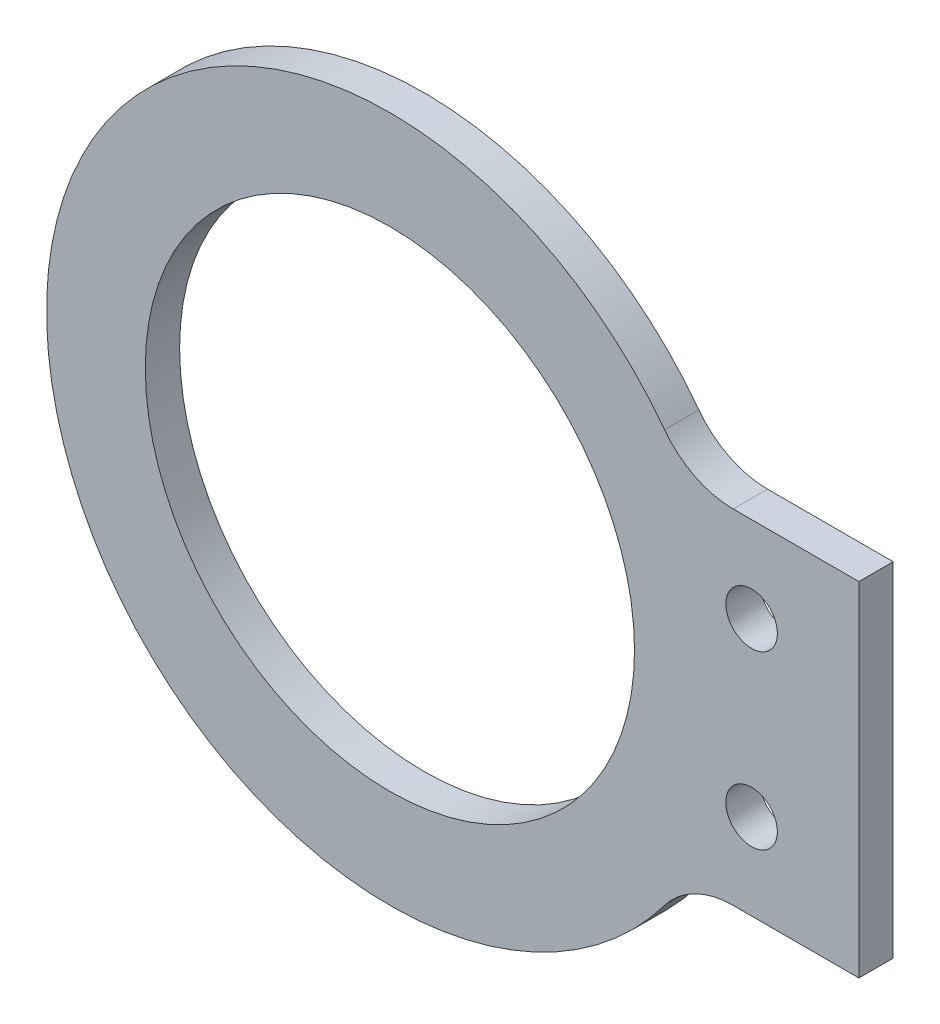
SolidWorks part; units mm, degrees
ref_plane "Plan de face" through (0, 0, 0) normal (0, 0, 1) x (1, 0, 0)
ref_plane "Plan de dessus" through (0, 0, 0) normal (0, 1, 0) x (1, 0, 0)
ref_plane "Plan de droite" through (0, 0, 0) normal (1, 0, 0) x (0, 0, -1)
sketch "Esquisse2" plane through (0, 0, 0) normal (0, 0, 1) x (1, 0, 0)
  line L0 (54.641, 0) -> (34.641, 0) construction
  line L1 (40, 20) -> (54.641, 20)
  line L2 (34.641, 20) -> (34.641, -20) construction
  line L3 (40, -20) -> (54.641, -20)
  line L4 (54.641, 20) -> (54.641, -20)
  line L5 (54.641, 16) -> (34.641, 16) construction
  line L6 (54.641, 16) -> (54.641, 4) construction
  line L7 (54.641, 4) -> (34.641, 4) construction
  line L8 (34.641, 16) -> (34.641, 4) construction
  circle A0 centre (0, 0) radius 28.5
  arc A1 (32, 24) -> (32, -24) centre (0, 0) ccw
  circle A2 centre (42.141, 10) radius 3
  circle A3 centre (42.141, -10) radius 3
  arc A4 (32, -24) -> (40, -20) centre (40, -30) cw
  arc A5 (40, 20) -> (32, 24) centre (40, 30) cw
  point P8 (34.641, 10)
  point P9 (54.641, 0)
  dimension "D1" = 57
  dimension "D2" = 80
  dimension "D6" = 6
  dimension "D10" = 10
  dimension "D3" = 20
  dimension "D4" = 20
  dimension "D5" = 12
  dimension "D7" = 7.5
  dimension "D8" = 40
  dimension "D9" = 10
extrude "Boss.-Extru.1" add sketch "Esquisse2" along normal blind 4
